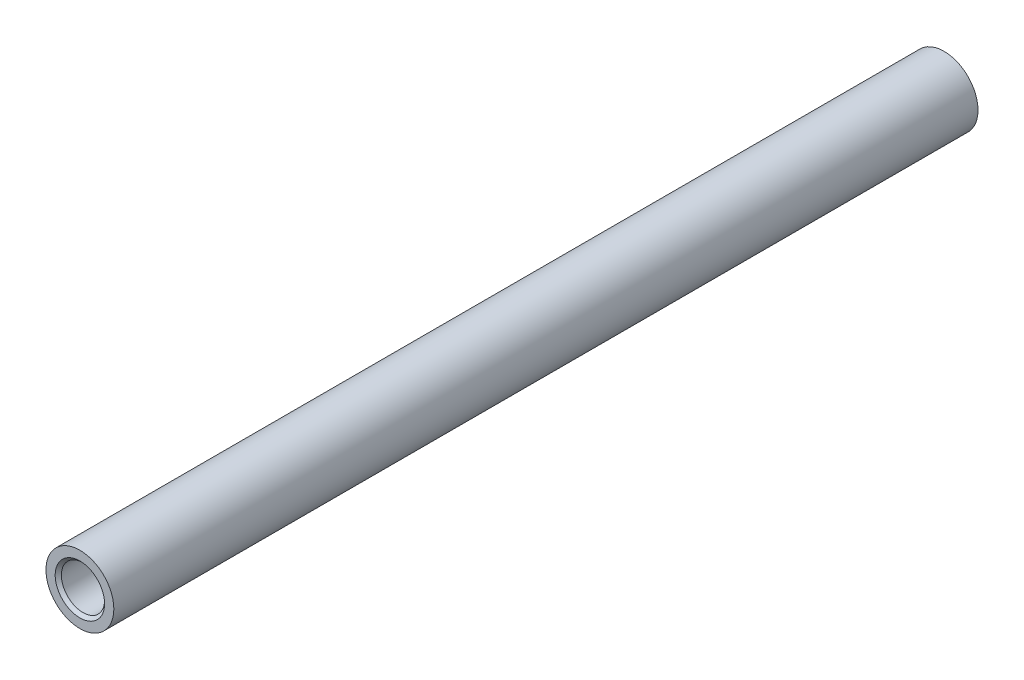
SolidWorks part; units mm, degrees
material "1.0545 (S355N)"
ref_plane "Płaszczyzna przednia" through (0, 0, 0) normal (0, 0, 1) x (1, 0, 0)
ref_plane "Płaszczyzna górna" through (0, 0, 0) normal (0, 1, 0) x (1, 0, 0)
ref_plane "Płaszczyzna prawa" through (0, 0, 0) normal (1, 0, 0) x (0, 0, -1)
sketch "Szkic1" plane through (0, 0, 0) normal (0, 0, 1) x (1, 0, 0)
  circle A0 centre (0, 0) radius 11
  circle A1 centre (0, 0) radius 7
  dimension "D1" = 22
  dimension "D2" = 4
extrude "Dodanie-wyciągnięcie1" add sketch "Szkic1" along normal mid plane 280
sketch "Szkic2" plane through (0, 0, -140) normal (0, 0, -1) x (-1, 0, 0)
  circle A0 centre (0, 0) radius 8
  circle A1 centre (0, 0) radius 7 construction
  dimension "D1" = 1
extrude "Wytnij-wyciągnięcie1" cut sketch "Szkic2" against normal blind 50
chamfer "Sfazowanie1" distance 1 angle 45 1 edges at (7, 0, 140)
